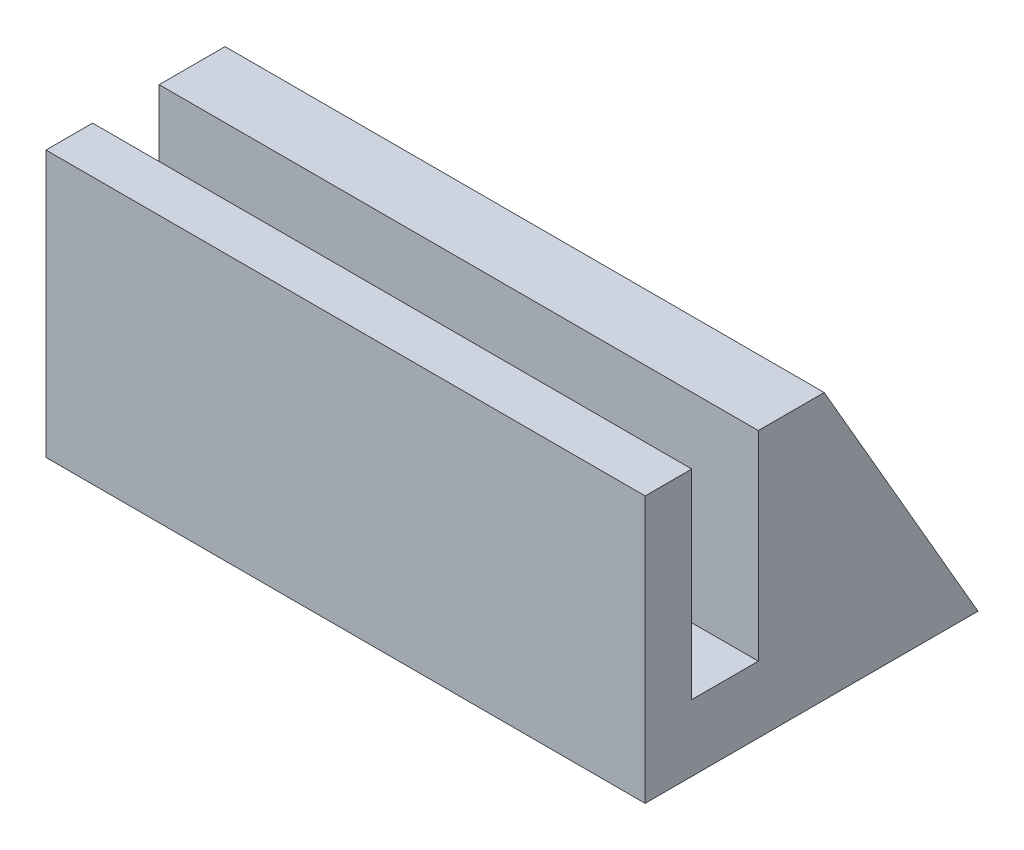
SolidWorks part; units mm, degrees
ref_plane "Front Plane" through (0, 0, 0) normal (0, 0, 1) x (1, 0, 0)
ref_plane "Top Plane" through (0, 0, 0) normal (0, 1, 0) x (1, 0, 0)
ref_plane "Right Plane" through (0, 0, 0) normal (1, 0, 0) x (0, 0, -1)
sketch "Sketch2" plane through (0, 0, 0) normal (0, 0, 1) x (1, 0, 0)
  line L1 (-22.5, -10) -> (22.5, -10)
  line L2 (-22.5, -10) -> (-22.5, 10)
  line L3 (-22.5, 10) -> (22.5, 10)
  line L4 (22.5, -10) -> (22.5, 10)
  line L5 (-22.5, -10) -> (22.5, 10) construction
  line L6 (-22.5, 10) -> (22.5, -10) construction
  point P0 (0, 0)
  dimension "D1" = 45
  dimension "D2" = 20
extrude "Boss-Extrude1" add sketch "Sketch2" along normal blind 25
sketch "Sketch5" plane through (0, 10, 0) normal (0, 1, 0) x (1, 0, 0)
  line L0 (0, 0) -> (0, -15)
  line L1 (0, -15) -> (0, -19)
  line L2 (22.5, -25) -> (22.5, 0) construction
  line L3 (-22.5, -16.5) -> (22.5, -16.5)
  line L4 (-22.5, -16.5) -> (-22.5, -21.5)
  line L5 (-22.5, -21.5) -> (22.5, -21.5)
  line L6 (22.5, -16.5) -> (22.5, -21.5)
  line L7 (-22.5, -16.5) -> (22.5, -21.5) construction
  line L8 (-22.5, -21.5) -> (22.5, -16.5) construction
  dimension "D1" = 15
  dimension "D2" = 4
  dimension "D3" = 5
extrude "Cut-Extrude1" cut sketch "Sketch5" against normal blind 15
sketch "Sketch7" plane through (22.5, 0, 0) normal (1, 0, 0) x (0, 0, -1)
  line L0 (0, -10) -> (0, 10)
  line L1 (0, 10) -> (-11.55, 10)
  line L2 (-16.5, 10) -> (0, 10) construction
  line L3 (-11.55, 10) -> (0, -10)
  dimension "D1" = 11.55
extrude "Cut-Extrude2" cut sketch "Sketch7" against normal up to surface (45 mm away) up to face at (-22.5, 1.25, 15.75)
sketch "Sketch8" plane through (0, -2.501, 4.3307) normal (0, 0.5001, -0.866) x (-1, 0, 0)
  line L1 (-19.15, -4.8) -> (19.15, -4.8)
  line L2 (-19.15, -4.8) -> (-19.15, 4.8)
  line L3 (-19.15, 4.8) -> (19.15, 4.8)
  line L4 (19.15, -4.8) -> (19.15, 4.8)
  line L5 (-19.15, -4.8) -> (19.15, 4.8) construction
  line L6 (-19.15, 4.8) -> (19.15, -4.8) construction
  point P0 (0, 0)
  dimension "D1" = 38.3
  dimension "D2" = 9.6
extrude "Cut-Extrude3" cut sketch "Sketch8" against normal blind 10
